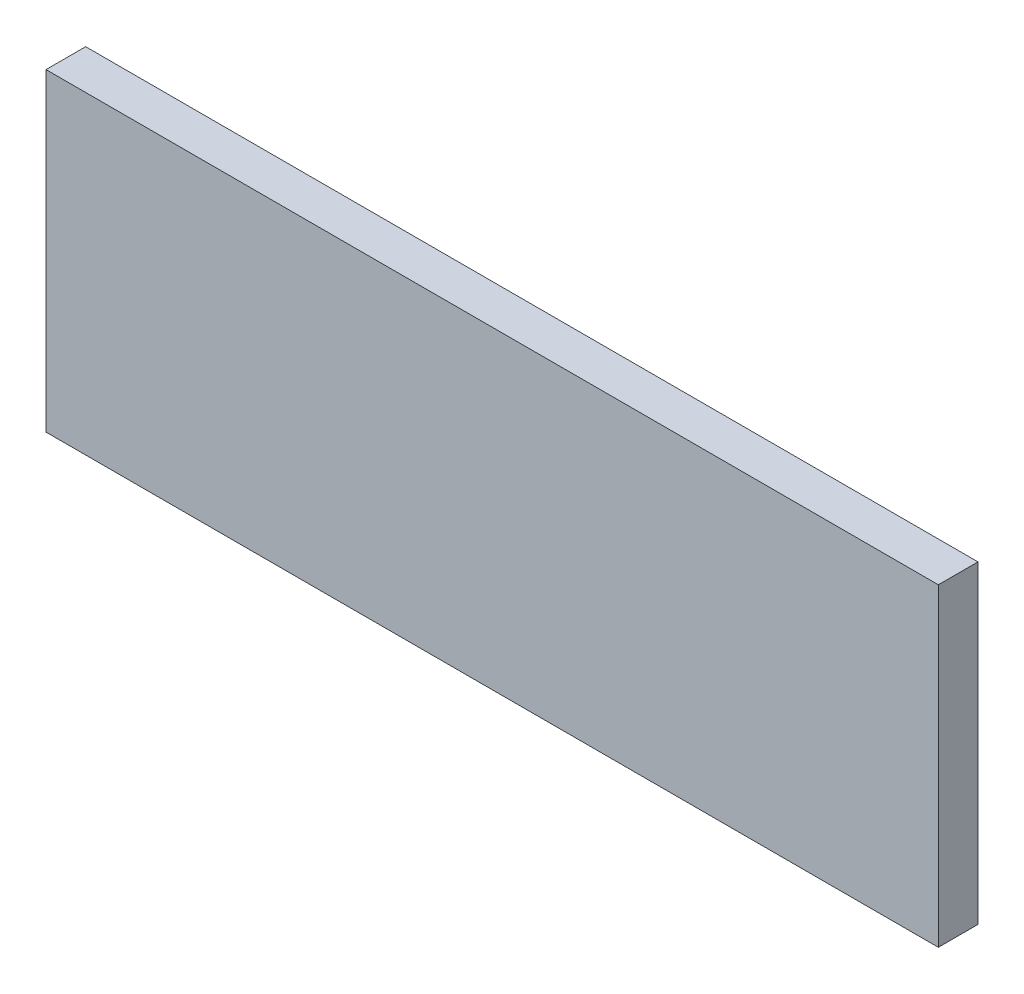
SolidWorks part; units mm, degrees
material "A516-Gr 70"
ref_plane "Front Plane" through (0, 0, 0) normal (0, 0, 1) x (1, 0, 0)
ref_plane "Top Plane" through (0, 0, 0) normal (0, 1, 0) x (1, 0, 0)
ref_plane "Right Plane" through (0, 0, 0) normal (1, 0, 0) x (0, 0, -1)
sketch "Sketch1" plane through (0, 0, 0) normal (0, 0, 1) x (1, 0, 0)
  line L1 (-135, -47.5) -> (135, -47.5)
  line L2 (-135, -47.5) -> (-135, 47.5)
  line L3 (-135, 47.5) -> (135, 47.5)
  line L4 (135, -47.5) -> (135, 47.5)
  line L5 (-135, -47.5) -> (135, 47.5) construction
  line L6 (-135, 47.5) -> (135, -47.5) construction
  point P0 (0, 0)
  dimension "D1" = 95
  dimension "D2" = 270
extrude "Boss-Extrude1" add sketch "Sketch1" along normal mid plane 12
